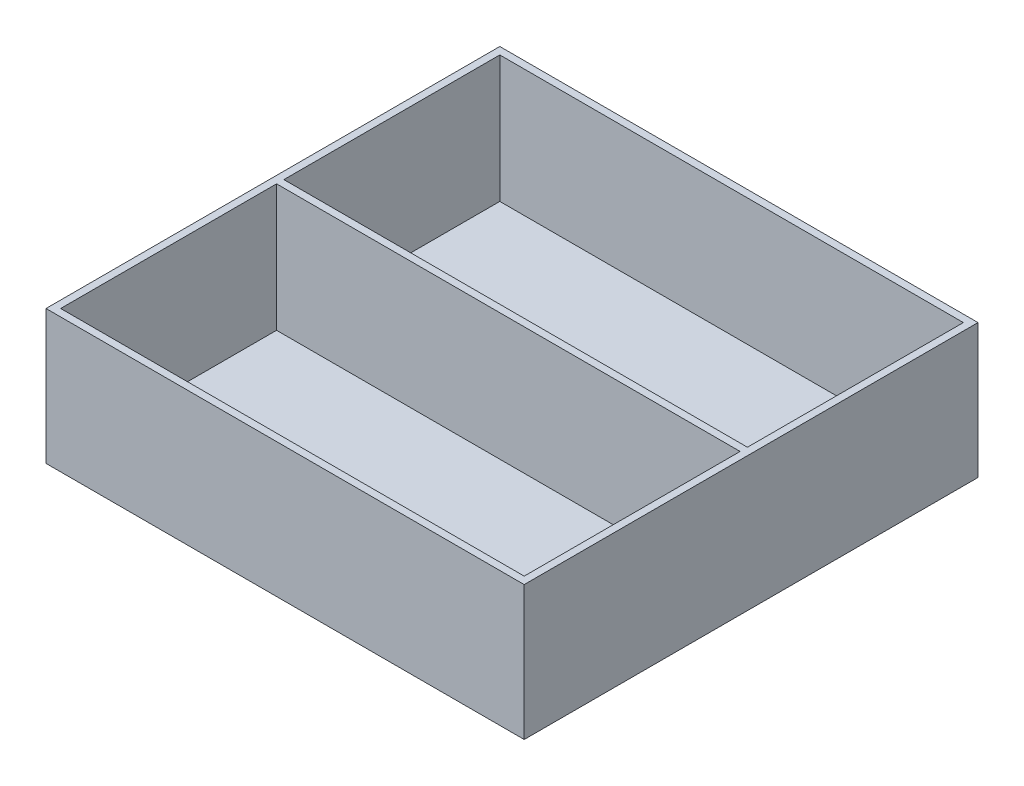
SolidWorks part; units mm, degrees
ref_plane "Front Plane" through (0, 0, 0) normal (0, 0, 1) x (1, 0, 0)
ref_plane "Top Plane" through (0, 0, 0) normal (0, 1, 0) x (1, 0, 0)
ref_plane "Right Plane" through (0, 0, 0) normal (1, 0, 0) x (0, 0, -1)
sketch "Sketch1" plane through (0, 0, 0) normal (0, 1, 0) x (1, 0, 0)
  line L1 (-98, -93) -> (98, -93)
  line L2 (-98, -93) -> (-98, 93)
  line L3 (-98, 93) -> (98, 93)
  line L4 (98, -93) -> (98, 93)
  line L5 (-98, -93) -> (98, 93) construction
  line L6 (-98, 93) -> (98, -93) construction
  point P0 (0, 0)
  dimension "D1" = 196
  dimension "D2" = 186
extrude "Boss-Extrude1" add sketch "Sketch1" along normal blind 55
sketch "Sketch2" plane through (0, 55, 0) normal (0, 1, 0) x (1, 0, 0)
  line L0 (-98, -93) -> (98, -93) construction
  line L1 (-95, -90) -> (95, -90)
  line L2 (-95, -90) -> (-95, -1.5)
  line L3 (-95, -1.5) -> (95, -1.5)
  line L4 (95, -90) -> (95, -1.5)
  line L5 (-95, -90) -> (95, -1.5) construction
  line L6 (-95, -1.5) -> (95, -90) construction
  line L7 (98, -93) -> (98, 93) construction
  line L8 (-98, 93) -> (-98, -93) construction
  line L9 (98, 93) -> (-98, 93) construction
  line L10 (-95, 1.5) -> (95, 1.5)
  line L11 (-95, 1.5) -> (-95, 90)
  line L12 (-95, 90) -> (95, 90)
  line L13 (95, 1.5) -> (95, 90)
  line L14 (-95, 1.5) -> (95, 90) construction
  line L15 (-95, 90) -> (95, 1.5) construction
  point P0 (0, -45.75)
  point P11 (0, 45.75)
  dimension "D1" = 3
  dimension "D2" = 3
  dimension "D3" = 3
  dimension "D4" = 3
  dimension "D5" = 3
  dimension "D6" = 3
  dimension "D7" = 3
  dimension "D8" = 88.5
extrude "Cut-Extrude1" cut sketch "Sketch2" against normal blind 52
